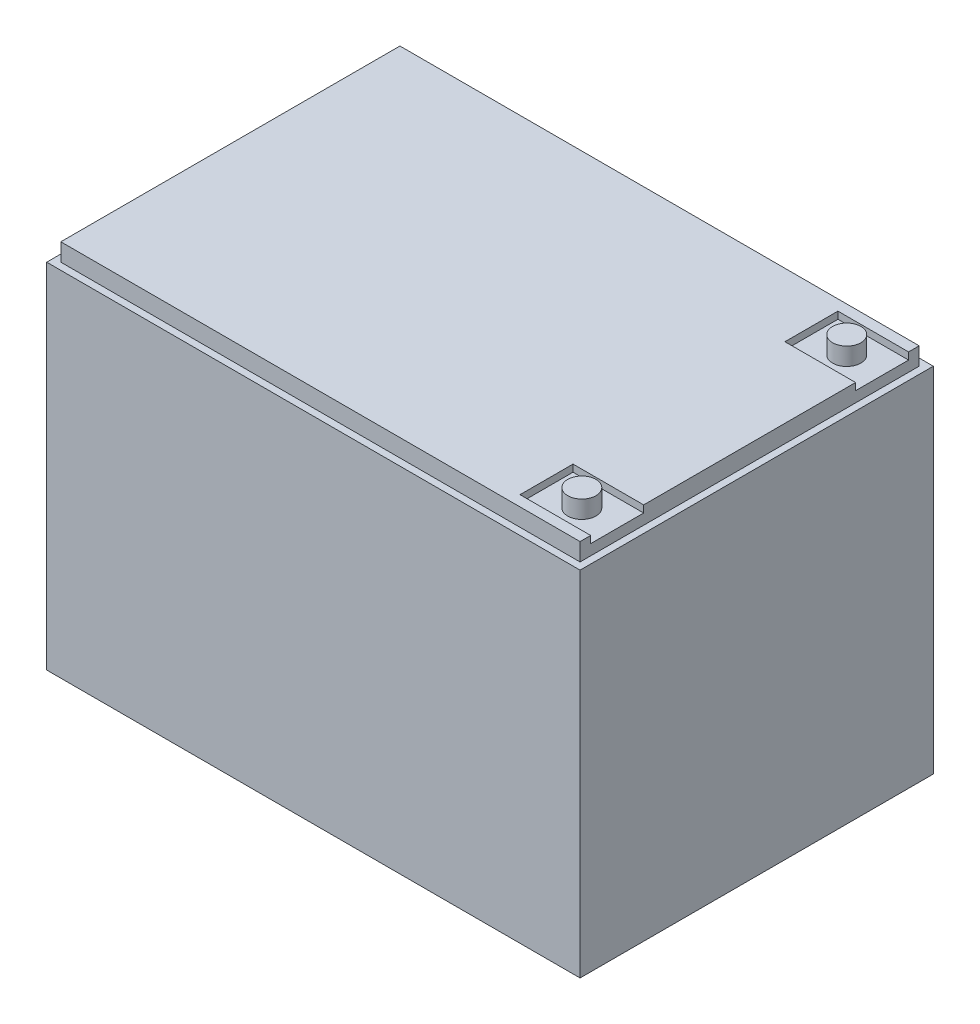
SolidWorks part; units mm, degrees
ref_plane "Front Plane" through (0, 0, 0) normal (0, 0, 1) x (1, 0, 0)
ref_plane "Top Plane" through (0, 0, 0) normal (0, 1, 0) x (1, 0, 0)
ref_plane "Right Plane" through (0, 0, 0) normal (1, 0, 0) x (0, 0, -1)
sketch "Sketch1" plane through (0, 0, 0) normal (0, 1, 0) x (1, 0, 0)
  line L1 (-75.5, -50) -> (75.5, -50)
  line L2 (-75.5, -50) -> (-75.5, 50)
  line L3 (-75.5, 50) -> (75.5, 50)
  line L4 (75.5, -50) -> (75.5, 50)
  line L5 (-75.5, -50) -> (75.5, 50) construction
  line L6 (-75.5, 50) -> (75.5, -50) construction
  point P0 (0, 0)
  dimension "D1" = 100
  dimension "D2" = 151
extrude "Boss-Extrude1" add sketch "Sketch1" along normal blind 105
sketch "Sketch2" plane through (0, 105, 0) normal (0, 1, 0) x (1, 0, 0)
  line L0 (73.5, 48) -> (-73.5, 48)
  line L1 (-73.5, 48) -> (-73.5, -48)
  line L2 (-73.5, -48) -> (73.5, -48)
  line L3 (73.5, -48) -> (73.5, 48)
  line L4 (75.5, -50) -> (75.5, 50)
  line L5 (75.5, 50) -> (-75.5, 50)
  line L6 (-75.5, 50) -> (-75.5, -50)
  line L7 (-75.5, -50) -> (75.5, -50)
  line L8 (75.5, -50) -> (75.5, 50)
  line L9 (75.5, 50) -> (-75.5, 50)
  line L10 (-75.5, 50) -> (-75.5, -50)
  line L11 (-75.5, -50) -> (75.5, -50)
  dimension "D1" = 0
  dimension "D2" = 2
extrude "Cut-Extrude1" cut sketch "Sketch2" against normal blind 5
sketch "Sketch3" plane through (0, 105, 0) normal (0, 1, 0) x (1, 0, 0)
  line L0 (73.5, -48) -> (73.5, 48) construction
  line L1 (73.5, 45) -> (53.5, 45)
  line L2 (73.5, 45) -> (73.5, 30)
  line L3 (73.5, 30) -> (53.5, 30)
  line L4 (53.5, 45) -> (53.5, 30)
  line L5 (0, 0) -> (98.6474, 0) construction
  line L6 (73.5, 48) -> (-73.5, 48) construction
  line L7 (73.5, -30) -> (53.5, -30)
  line L8 (53.5, -45) -> (53.5, -30)
  line L9 (73.5, -45) -> (53.5, -45)
  line L10 (73.5, -45) -> (73.5, -30)
  dimension "D1" = 3
  dimension "D2" = 15
  dimension "D3" = 20
extrude "Cut-Extrude2" cut sketch "Sketch3" against normal blind 2
sketch "Sketch4" plane through (0, 103, 0) normal (0, 1, 0) x (1, 0, 0)
  line L0 (0, 0) -> (90.3092, 0) construction
  line L1 (53.5, -30) -> (73.5, -45) construction
  circle A0 centre (63.5, -37.5) radius 4
  circle A1 centre (63.5, 37.5) radius 4
  dimension "D1" = 8
extrude "Boss-Extrude2" add sketch "Sketch4" along normal blind 5
